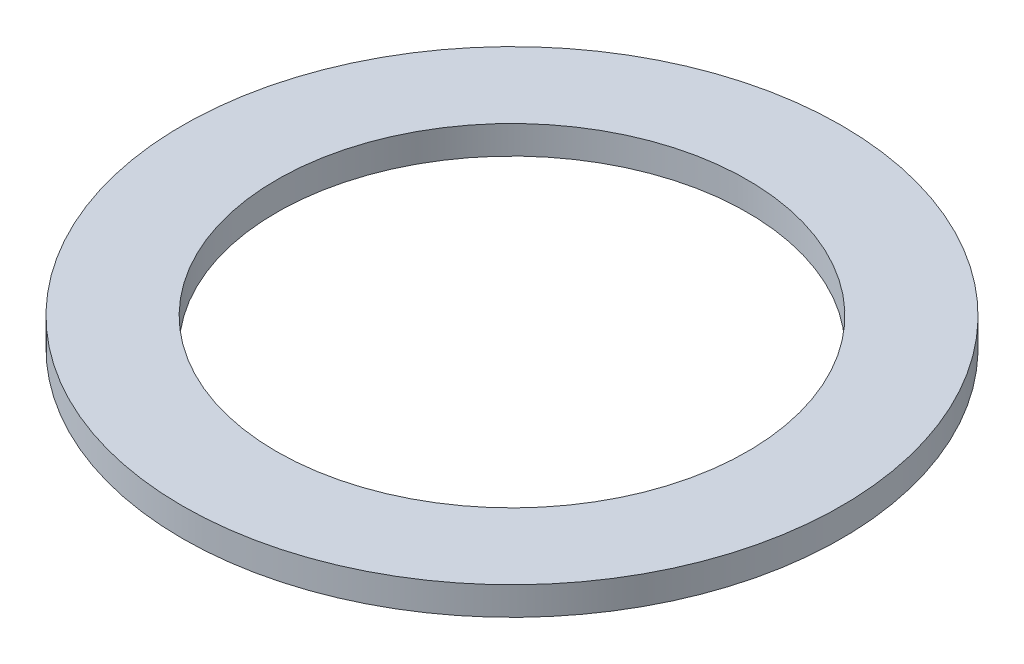
SolidWorks part; units mm, degrees
ref_plane "Front Plane" through (0, 0, 0) normal (0, 0, 1) x (1, 0, 0)
ref_plane "Top Plane" through (0, 0, 0) normal (0, 1, 0) x (1, 0, 0)
ref_plane "Right Plane" through (0, 0, 0) normal (1, 0, 0) x (0, 0, -1)
sketch "Sketch1" plane through (0, 0, 0) normal (0, 1, 0) x (1, 0, 0)
  circle A0 centre (0, 0) radius 2.5
  circle A1 centre (0, 0) radius 3.5
  dimension "D1" = 7
  dimension "D2" = 5
extrude "Boss-Extrude1" add sketch "Sketch1" along normal blind 0.3
